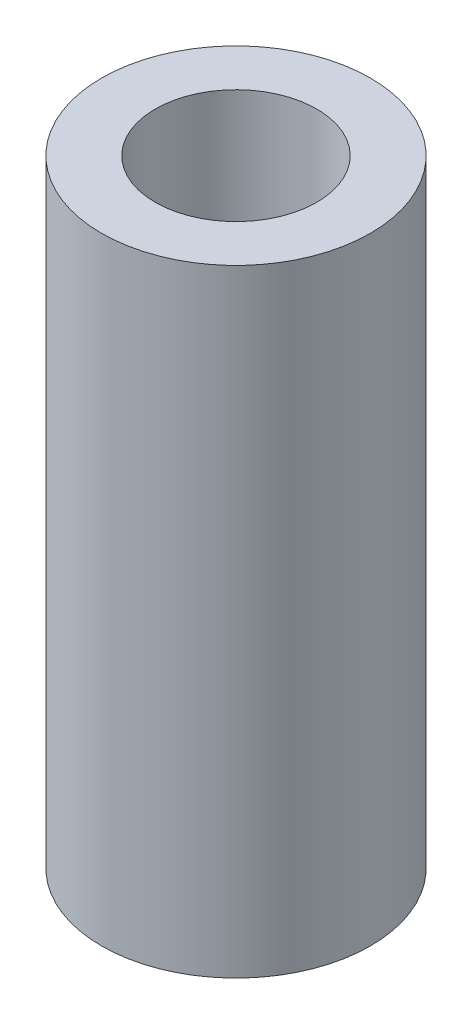
SolidWorks part; units mm, degrees
material "ABS"
ref_plane "Front Plane" through (0, 0, 0) normal (0, 0, 1) x (1, 0, 0)
ref_plane "Top Plane" through (0, 0, 0) normal (0, 1, 0) x (1, 0, 0)
ref_plane "Right Plane" through (0, 0, 0) normal (1, 0, 0) x (0, 0, -1)
sketch "Sketch1" plane through (0, 0, 0) normal (0, 1, 0) x (1, 0, 0)
  circle A0 centre (0, 0) radius 2.3813
  circle A1 centre (0, 0) radius 3.9624
  dimension "D1" = 4.7625
  dimension "D2" = 7.9248
extrude "Boss-Extrude1" add sketch "Sketch1" along normal mid plane 18.1898
